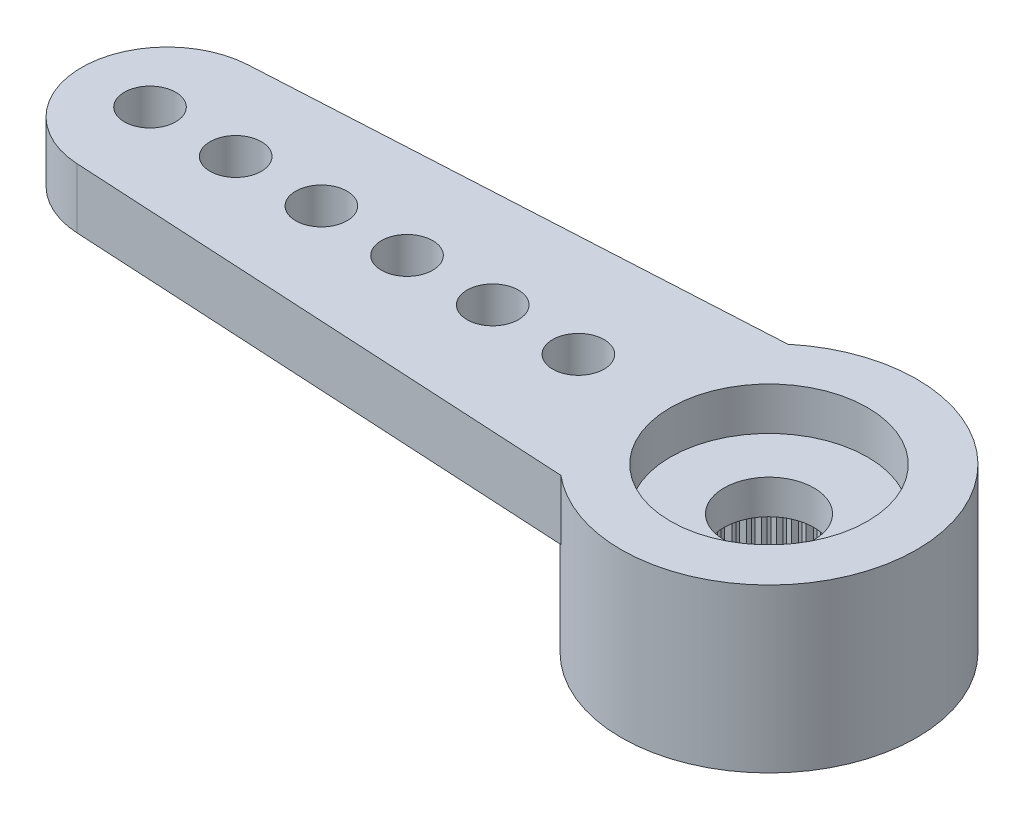
SolidWorks part; units mm, degrees
material "PVC Rígido"
ref_plane "Plano frontal" through (0, 0, 0) normal (0, 0, 1) x (1, 0, 0)
ref_plane "Plano superior" through (0, 0, 0) normal (0, 1, 0) x (1, 0, 0)
ref_plane "Plano direito" through (0, 0, 0) normal (1, 0, 0) x (0, 0, -1)
sketch "Esboço1" plane through (0, 0, 0) normal (0, 1, 0) x (1, 0, 0)
  line L0 (0, 0) -> (-14.05, 0) construction
  line L1 (-14.1591, 1.997) -> (-2.2091, 2.65)
  line L2 (-2.2091, -2.65) -> (-14.1591, -1.997)
  arc A0 (-2.2091, -2.65) -> (-2.2091, 2.65) centre (0, 0) ccw
  arc A1 (-14.1591, 1.997) -> (-14.1591, -1.997) centre (-14.05, 0) ccw
  dimension "D1" = 6.9
  dimension "D2" = 4
  dimension "D3" = 19.5
  dimension "D4" = 5.3
extrude "Ressalto-extrusão1" add sketch "Esboço1" against normal blind 1.4
sketch "Esboço2" plane through (0, -1.4, 0) normal (0, -1, 0) x (1, 0, 0)
  arc A0 (-2.2091, -2.65) -> (-2.2091, 2.65) centre (0, 0) ccw construction
  circle A1 centre (0, 0) radius 3.45
extrude "Ressalto-extrusão2" add sketch "Esboço2" along normal offset from surface (2.4 mm away) 3.8 up to face at (-7.242, 0, 0)
hole_wizard "Furo4" positions "Esboço9" profile "Esboço10" legacy end condition through all
sketch "Esboço9" plane through (0, 0, 0) normal (0, 1, 0) x (1, 0, 0)
  line L1 (-14.45, 0) -> (0, 0) construction
  arc A2 (-14.1591, 1.997) -> (-14.1591, -1.997) centre (-14.05, 0) ccw construction
  point P0 (-14.45, 0)
  point P19 (-16.05, 0)
  dimension "D1" = 1.6
sketch "Esboço10" plane through (-14.45, 0, 0) normal (1, 0, 0) x (0, 0, 1)
  line L0 (0, 0) -> (0, 3.8)
  line L1 (0, 3.8) -> (0.6, 3.8)
  line L2 (0.6, 3.8) -> (0.6, 0)
  line L3 (0.6, 0) -> (0, 0)
  line L4 (0, 110) -> (0, -10) construction
  dimension "Diameter" = 1.2
  dimension "Depth" = 3.8
pattern_linear "Padrão linear1" count 6 spacing 2 along (1, 0, 0) of "Furo4"
hole_wizard "Furo1" positions "Esboço3" profile "Esboço4" legacy
sketch "Esboço3" plane through (0, -3.8, 0) normal (0, -1, 0) x (-1, 0, 0)
  point P0 (0, 0)
sketch "Esboço4" plane through (0, -3.8, 0) normal (1, 0, 0) x (0, 0, -1)
  line L0 (0, 0) -> (0, 2)
  line L1 (0, 2) -> (2.475, 2)
  line L2 (2.475, 2) -> (2.475, 0)
  line L3 (2.475, 0) -> (0, 0)
  line L4 (0, 110) -> (0, -10) construction
  dimension "Diameter" = 4.95
  dimension "Depth" = 2
hole_wizard "Furo2" positions "Esboço5" profile "Esboço6" legacy
sketch "Esboço5" plane through (0, 0, 0) normal (0, 1, 0) x (1, 0, 0)
  point P0 (0, 0)
sketch "Esboço6" plane through (0, 0, 0) normal (1, 0, 0) x (0, 0, 1)
  line L0 (0, 0) -> (0, 1)
  line L1 (0, 1) -> (2.3, 1)
  line L2 (2.3, 1) -> (2.3, 0)
  line L3 (2.3, 0) -> (0, 0)
  line L4 (0, 110) -> (0, -10) construction
  dimension "Diameter" = 4.6
  dimension "Depth" = 1
hole_wizard "Furo3" positions "Esboço7" profile "Esboço8" legacy end condition through all
sketch "Esboço7" plane through (0, 0, 0) normal (0, 1, 0) x (1, 0, 0)
  point P0 (0, 0)
sketch "Esboço8" plane through (0, 0, 0) normal (1, 0, 0) x (0, 0, 1)
  line L0 (0, 0) -> (0, 3.8)
  line L1 (0, 3.8) -> (1.05, 3.8)
  line L2 (1.05, 3.8) -> (1.05, 0)
  line L3 (1.05, 0) -> (0, 0)
  line L4 (0, 110) -> (0, -10) construction
  dimension "Diameter" = 2.1
  dimension "Depth" = 3.8
sketch "Esboço11" plane through (0, -3.8, 0) normal (0, -1, 0) x (1, 0, 0)
  line L0 (-0.0981, 2.4731) -> (0, 2.375)
  line L1 (0, 2.375) -> (0.0981, 2.4731)
  line L2 (0, 0) -> (0, 2.475) construction
  circle A0 centre (0, 0) radius 2.375 construction
  circle A1 centre (0, 0) radius 2.475
  arc A2 (0.0981, 2.4731) -> (-0.0981, 2.4731) centre (0, 0) ccw
  dimension "D3" = 4.75
  dimension "D2" = 0.1
  dimension "D1" = 0
extrude "Ressalto-extrusão3" add sketch "Esboço11" against normal up to surface (2 mm away) up to face at (0, -1.8, 1.05)
pattern_circular "PadrãoCircular1" count 60 over 360 about axis through (0, 0, 0) along (0, 1, 0) of "Ressalto-extrusão3"
sketch "Sketch1" plane through (0, 0, 0) normal (0, 1, 0) x (1, 0, 0)
  line L0 (-16.05, 0) -> (-2.3, 0) construction
  arc A0 (-14.1591, 1.997) -> (-14.1591, -1.997) centre (-14.05, 0) ccw construction
  circle A1 centre (0, 0) radius 2.3 construction
